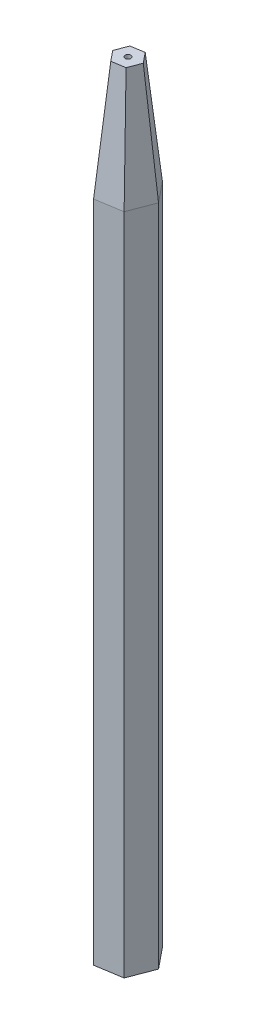
SolidWorks part; units mm, degrees
ref_plane "Ebene vorne" through (0, 0, 0) normal (0, 0, 1) x (1, 0, 0)
ref_plane "Ebene oben" through (0, 0, 0) normal (0, 1, 0) x (1, 0, 0)
ref_plane "Ebene rechts" through (0, 0, 0) normal (1, 0, 0) x (0, 0, -1)
sketch "Skizze1" plane through (0, 0, 0) normal (0, 1, 0) x (1, 0, 0)
  line L1 (2.9126, -3.5847) -> (4.5607, 0.73)
  line L2 (4.5607, 0.73) -> (1.6482, 4.3147)
  line L3 (1.6482, 4.3147) -> (-2.9126, 3.5847)
  line L4 (-2.9126, 3.5847) -> (-4.5607, -0.73)
  line L5 (-4.5607, -0.73) -> (-1.6482, -4.3147)
  line L6 (-1.6482, -4.3147) -> (2.9126, -3.5847)
  circle A0 centre (0, 0) radius 4 construction
  circle A1 centre (0, 0) radius 0.5
  dimension "D2" = 1
  dimension "D1" = 8
extrude "Aufsatz-Linear austragen1" add sketch "Skizze1" along normal blind 135
chamfer "Fase2" distance 20 distance2 2 6 edges at (-3.1045, 135, 2.5224) (-3.7367, 135, -1.4274) (-0.6322, 135, -3.9497) (3.1045, 135, -2.5224) (3.7367, 135, 1.4274) (0.6322, 135, 3.9497)
